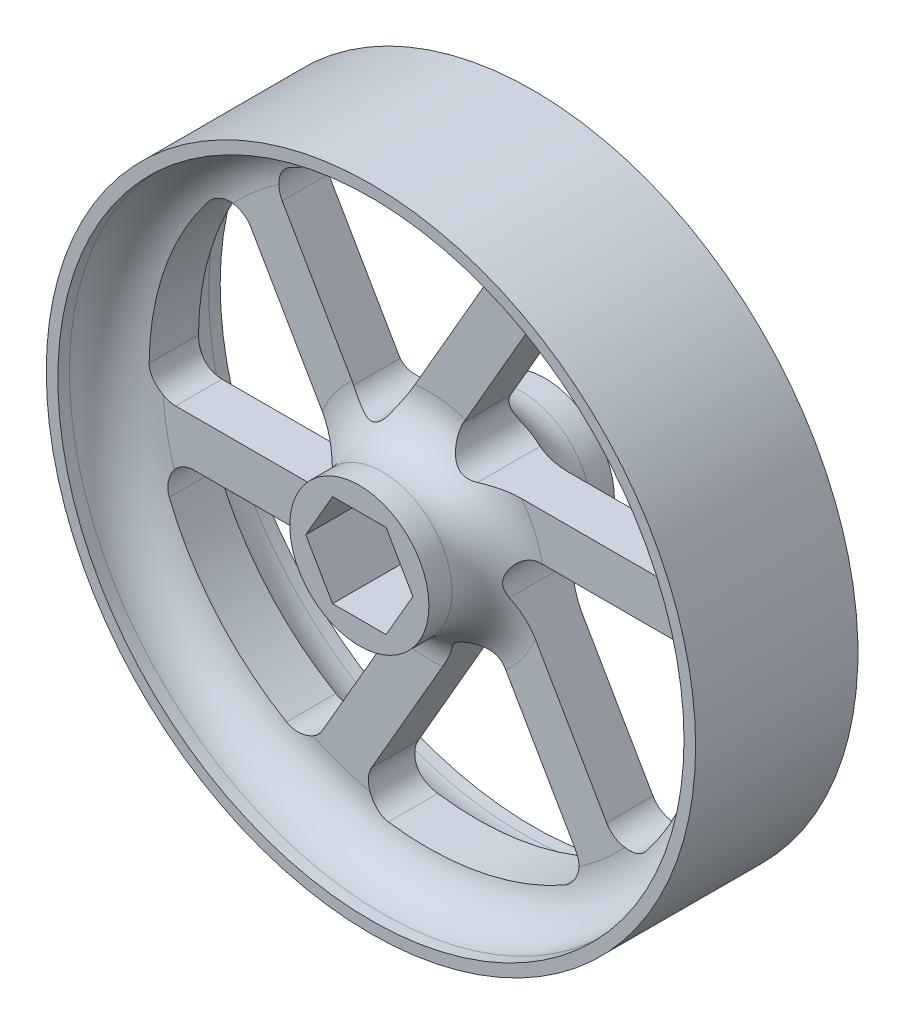
SolidWorks part; units mm, degrees
material "6061-T6 (SS)"
ref_plane "Front Plane" through (0, 0, 0) normal (0, 0, 1) x (1, 0, 0)
ref_plane "Top Plane" through (0, 0, 0) normal (0, 1, 0) x (1, 0, 0)
ref_plane "Right Plane" through (0, 0, 0) normal (1, 0, 0) x (0, 0, -1)
sketch "Sketch1" plane through (0, 0, 0) normal (0, 0, 1) x (1, 0, 0)
  line L1 (3.6662, -6.35) -> (7.3323, 0)
  line L2 (7.3323, 0) -> (3.6662, 6.35)
  line L3 (3.6662, 6.35) -> (-3.6662, 6.35)
  line L4 (-3.6662, 6.35) -> (-7.3323, 0)
  line L5 (-7.3323, 0) -> (-3.6662, -6.35)
  line L6 (-3.6662, -6.35) -> (3.6662, -6.35)
  circle A0 centre (0, 0) radius 44.45
  circle A1 centre (0, 0) radius 6.35 construction
  dimension "D1" = 88.9
  dimension "D2" = 12.7
extrude "Boss-Extrude1" add sketch "Sketch1" along normal mid plane 25.4
sketch "Sketch2" plane through (0, 0, 0) normal (0, 1, 0) x (1, 0, 0)
  line L0 (0, -1000) -> (0, 49000) construction
  line L1 (-1000, 0) -> (49000, 0) construction
  line L2 (-36.5125, 3.175) -> (-15.875, 3.175)
  line L3 (-42.8625, 9.525) -> (-42.8625, 12.7)
  line L4 (44.45, 12.7) -> (-44.45, 12.7) construction
  line L5 (-44.45, 12.7) -> (-44.45, -12.7) construction
  line L6 (-9.525, 9.525) -> (-9.525, 12.7)
  line L7 (-9.525, 12.7) -> (-42.8625, 12.7)
  arc A0 (-42.8625, 9.525) -> (-36.5125, 3.175) centre (-36.5125, 9.525) ccw
  arc A1 (-15.875, 3.175) -> (-9.525, 9.525) centre (-15.875, 9.525) ccw
  dimension "D1" = 12.7
  dimension "D2" = 6.35
  dimension "D3" = 1.5875
  dimension "D4" = 19.05
revolve "Cut-Revolve1" cut sketch "Sketch2" angle 360 about L0
mirror "Mirror1" about plane through (0, 0, 0) normal (0, 0, 1) of "Cut-Revolve1"
sketch "Sketch3" plane through (0, 0, 12.7) normal (0, 0, 1) x (1, 0, 0)
  circle A0 centre (0, 0) radius 27.1324
extrude "Cut-Extrude1" cut sketch "Sketch3" against normal blind 1.5875 flip side to cut
mirror "Mirror2" about plane through (0, 0, 0) normal (0, 0, 1) of "Cut-Extrude1"
sketch "Sketch4" plane through (0, 0, 3.175) normal (0, 0, 1) x (1, 0, 0)
  line L0 (0, 9.525) -> (29.3743, 9.525) construction
  line L1 (15.1046, 3.175) -> (34.6701, 3.175)
  line L2 (12.135, -1.9685) -> (24.3289, -23.089)
  arc A0 (29.9984, -23.4884) -> (38.099, -0.2791) centre (0, 0) ccw
  circle A1 centre (0, 0) radius 9.525 construction
  arc A2 (12.135, -1.9685) -> (15.1046, 3.175) centre (15.1046, -0.254) cw
  circle A3 centre (0, 0) radius 9.525 construction
  circle A4 centre (0, 0) radius 44.45 construction
  arc A5 (24.3289, -23.089) -> (29.9984, -23.4884) centre (27.2985, -21.3745) ccw
  arc A6 (34.6701, 3.175) -> (38.099, -0.2791) centre (34.6701, -0.254) cw
  point P2 (-3.175, 8.9803)
  point P12 (0, 0)
  point P13 (31.7098, 23.7181)
  point P14 (36.6381, 9.3924)
  point P22 (13.1196, 27.4813)
  dimension "D4" = 6.35
  dimension "D2" = 3.429
  dimension "D1" = 6.35
  dimension "D3" = 60
extrude "Cut-Extrude2" cut sketch "Sketch4" against normal through all both and the other way through all
pattern_circular "CirPattern1" count 6 over 360 about axis through (0, 0, 0) along (0, 0, 1) of "Cut-Extrude2"
